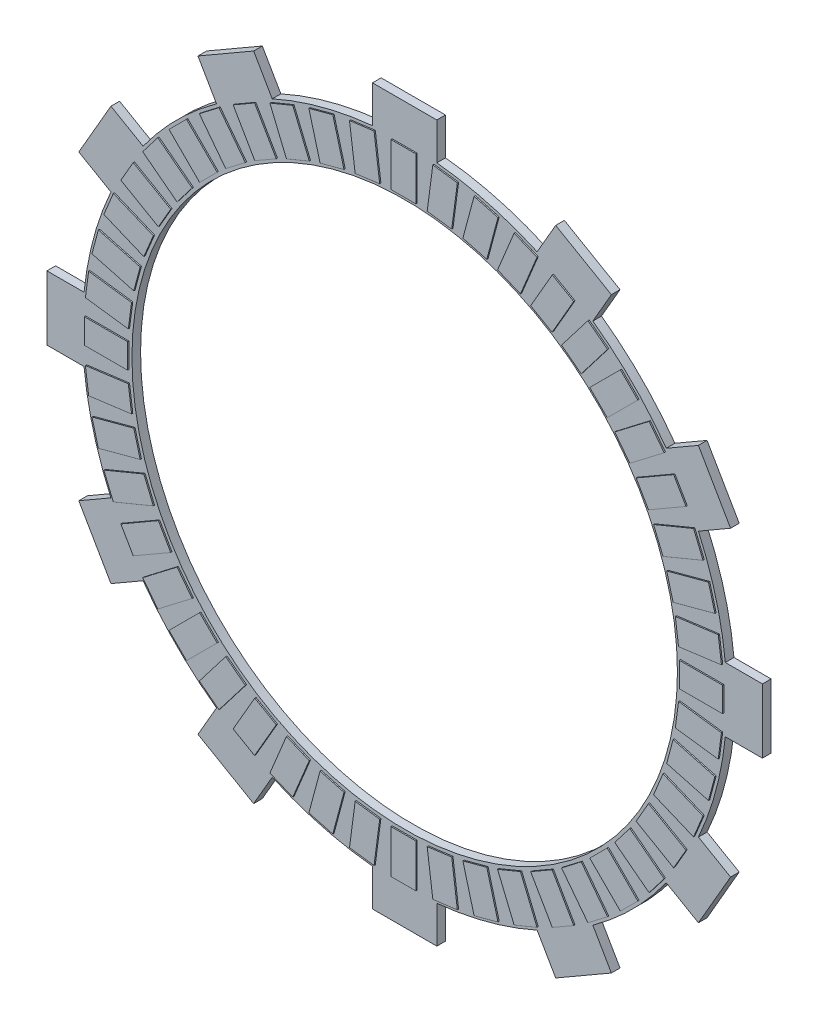
SolidWorks part; units mm, degrees
material "Plain Carbon Steel"
ref_plane "Front Plane" through (0, 0, 0) normal (0, 0, 1) x (1, 0, 0)
ref_plane "Top Plane" through (0, 0, 0) normal (0, 1, 0) x (1, 0, 0)
ref_plane "Right Plane" through (0, 0, 0) normal (1, 0, 0) x (0, 0, -1)
sketch "Sketch1" plane through (0, 0, 0) normal (0, 0, 1) x (1, 0, 0)
  line L0 (0, 0) -> (0, 94.1229) construction
  line L1 (-6.604, 65.8366) -> (-6.604, 73.4566)
  line L2 (-6.604, 73.4566) -> (6.604, 73.4566)
  line L3 (6.604, 73.4566) -> (6.604, 65.8366)
  line L4 (42.4475, 60.3133) -> (38.6375, 53.7142)
  line L5 (27.1991, 60.3182) -> (31.0091, 66.9173)
  line L6 (31.0091, 66.9173) -> (42.4475, 60.3133)
  line L7 (66.9173, 31.0091) -> (60.3182, 27.1991)
  line L8 (53.7142, 38.6375) -> (60.3133, 42.4475)
  line L9 (60.3133, 42.4475) -> (66.9173, 31.0091)
  line L10 (73.4566, -6.604) -> (65.8366, -6.604)
  line L11 (65.8366, 6.604) -> (73.4566, 6.604)
  line L12 (73.4566, 6.604) -> (73.4566, -6.604)
  line L13 (60.3133, -42.4475) -> (53.7142, -38.6375)
  line L14 (60.3182, -27.1991) -> (66.9173, -31.0091)
  line L15 (66.9173, -31.0091) -> (60.3133, -42.4475)
  line L16 (31.0091, -66.9173) -> (27.1991, -60.3182)
  line L17 (38.6375, -53.7142) -> (42.4475, -60.3133)
  line L18 (42.4475, -60.3133) -> (31.0091, -66.9173)
  line L19 (-6.604, -73.4566) -> (-6.604, -65.8366)
  line L20 (6.604, -65.8366) -> (6.604, -73.4566)
  line L21 (6.604, -73.4566) -> (-6.604, -73.4566)
  line L22 (-42.4475, -60.3133) -> (-38.6375, -53.7142)
  line L23 (-27.1991, -60.3182) -> (-31.0091, -66.9173)
  line L24 (-31.0091, -66.9173) -> (-42.4475, -60.3133)
  line L25 (-66.9173, -31.0091) -> (-60.3182, -27.1991)
  line L26 (-53.7142, -38.6375) -> (-60.3133, -42.4475)
  line L27 (-60.3133, -42.4475) -> (-66.9173, -31.0091)
  line L28 (-73.4566, 6.604) -> (-65.8366, 6.604)
  line L29 (-65.8366, -6.604) -> (-73.4566, -6.604)
  line L30 (-73.4566, -6.604) -> (-73.4566, 6.604)
  line L31 (-60.3133, 42.4475) -> (-53.7142, 38.6375)
  line L32 (-60.3182, 27.1991) -> (-66.9173, 31.0091)
  line L33 (-66.9173, 31.0091) -> (-60.3133, 42.4475)
  line L34 (-31.0091, 66.9173) -> (-27.1991, 60.3182)
  line L35 (-38.6375, 53.7142) -> (-42.4475, 60.3133)
  line L36 (-42.4475, 60.3133) -> (-31.0091, 66.9173)
  arc A0 (-6.604, 65.8366) -> (-27.1991, 60.3182) centre (0, 0) ccw
  circle A1 centre (0, 0) radius 56.007
  arc A2 (-38.6375, 53.7142) -> (-53.7142, 38.6375) centre (0, 0) ccw
  arc A3 (-60.3182, 27.1991) -> (-65.8366, 6.604) centre (0, 0) ccw
  arc A4 (-65.8366, -6.604) -> (-60.3182, -27.1991) centre (0, 0) ccw
  arc A5 (-53.7142, -38.6375) -> (-38.6375, -53.7142) centre (0, 0) ccw
  arc A6 (-27.1991, -60.3182) -> (-6.604, -65.8366) centre (0, 0) ccw
  arc A7 (6.604, -65.8366) -> (27.1991, -60.3182) centre (0, 0) ccw
  arc A8 (38.6375, -53.7142) -> (53.7142, -38.6375) centre (0, 0) ccw
  arc A9 (60.3182, -27.1991) -> (65.8366, -6.604) centre (0, 0) ccw
  arc A10 (65.8366, 6.604) -> (60.3182, 27.1991) centre (0, 0) ccw
  arc A11 (53.7142, 38.6375) -> (38.6375, 53.7142) centre (0, 0) ccw
  arc A12 (27.1991, 60.3182) -> (6.604, 65.8366) centre (0, 0) ccw
  point P8 (0, 73.4566)
  point P56 (0, 0)
  dimension "D1" = 10.16
  dimension "D2" = 112.014
  dimension "D3" = 13.208
  dimension "D4" = 7.62
  dimension "D5" = 12
extrude "Boss-Extrude1" add sketch "Sketch1" along normal blind 1.778
sketch "Sketch2" plane through (0, 0, 1.778) normal (0, 0, 1) x (1, 0, 0)
  line L0 (0, 0) -> (0, 131.064) construction
  line L1 (-2.54, 65.532) -> (2.54, 65.532)
  line L2 (2.54, 65.532) -> (2.54, 56.642)
  line L3 (2.54, 56.642) -> (-2.54, 56.642)
  line L4 (-2.54, 56.642) -> (-2.54, 65.532)
  line L5 (4.875, 56.489) -> (6.0354, 65.3029)
  line L6 (6.0354, 65.3029) -> (11.0719, 64.6398)
  line L7 (11.0719, 64.6398) -> (9.9115, 55.8259)
  line L8 (9.9115, 55.8259) -> (4.875, 56.489)
  line L9 (12.2066, 55.3694) -> (14.5075, 63.9565)
  line L10 (14.5075, 63.9565) -> (19.4144, 62.6417)
  line L11 (19.4144, 62.6417) -> (17.1135, 54.0546)
  line L12 (17.1135, 54.0546) -> (12.2066, 55.3694)
  line L13 (19.3293, 53.3024) -> (22.7314, 61.5157)
  line L14 (22.7314, 61.5157) -> (27.4247, 59.5717)
  line L15 (27.4247, 59.5717) -> (24.0226, 51.3584)
  line L16 (24.0226, 51.3584) -> (19.3293, 53.3024)
  line L17 (26.1213, 50.3234) -> (30.5663, 58.0224)
  line L18 (30.5663, 58.0224) -> (34.9657, 55.4824)
  line L19 (34.9657, 55.4824) -> (30.5207, 47.7834)
  line L20 (30.5207, 47.7834) -> (26.1213, 50.3234)
  line L21 (32.4663, 46.4834) -> (37.8782, 53.5363)
  line L22 (37.8782, 53.5363) -> (41.9085, 50.4438)
  line L23 (41.9085, 50.4438) -> (36.4966, 43.3909)
  line L24 (36.4966, 43.3909) -> (32.4663, 46.4834)
  line L25 (38.2559, 41.848) -> (44.5421, 48.1342)
  line L26 (44.5421, 48.1342) -> (48.1342, 44.5421)
  line L27 (48.1342, 44.5421) -> (41.848, 38.2559)
  line L28 (41.848, 38.2559) -> (38.2559, 41.848)
  line L29 (43.3909, 36.4966) -> (50.4438, 41.9085)
  line L30 (50.4438, 41.9085) -> (53.5363, 37.8782)
  line L31 (53.5363, 37.8782) -> (46.4834, 32.4663)
  line L32 (46.4834, 32.4663) -> (43.3909, 36.4966)
  line L33 (47.7834, 30.5207) -> (55.4824, 34.9657)
  line L34 (55.4824, 34.9657) -> (58.0224, 30.5663)
  line L35 (58.0224, 30.5663) -> (50.3234, 26.1213)
  line L36 (50.3234, 26.1213) -> (47.7834, 30.5207)
  line L37 (51.3584, 24.0226) -> (59.5717, 27.4247)
  line L38 (59.5717, 27.4247) -> (61.5157, 22.7314)
  line L39 (61.5157, 22.7314) -> (53.3024, 19.3293)
  line L40 (53.3024, 19.3293) -> (51.3584, 24.0226)
  line L41 (54.0546, 17.1135) -> (62.6417, 19.4144)
  line L42 (62.6417, 19.4144) -> (63.9565, 14.5075)
  line L43 (63.9565, 14.5075) -> (55.3694, 12.2066)
  line L44 (55.3694, 12.2066) -> (54.0546, 17.1135)
  line L45 (55.8259, 9.9115) -> (64.6398, 11.0719)
  line L46 (64.6398, 11.0719) -> (65.3029, 6.0354)
  line L47 (65.3029, 6.0354) -> (56.489, 4.875)
  line L48 (56.489, 4.875) -> (55.8259, 9.9115)
  line L49 (56.642, 2.54) -> (65.532, 2.54)
  line L50 (65.532, 2.54) -> (65.532, -2.54)
  line L51 (65.532, -2.54) -> (56.642, -2.54)
  line L52 (56.642, -2.54) -> (56.642, 2.54)
  line L53 (56.489, -4.875) -> (65.3029, -6.0354)
  line L54 (65.3029, -6.0354) -> (64.6398, -11.0719)
  line L55 (64.6398, -11.0719) -> (55.8259, -9.9115)
  line L56 (55.8259, -9.9115) -> (56.489, -4.875)
  line L57 (55.3694, -12.2066) -> (63.9565, -14.5075)
  line L58 (63.9565, -14.5075) -> (62.6417, -19.4144)
  line L59 (62.6417, -19.4144) -> (54.0546, -17.1135)
  line L60 (54.0546, -17.1135) -> (55.3694, -12.2066)
  line L61 (53.3024, -19.3293) -> (61.5157, -22.7314)
  line L62 (61.5157, -22.7314) -> (59.5717, -27.4247)
  line L63 (59.5717, -27.4247) -> (51.3584, -24.0226)
  line L64 (51.3584, -24.0226) -> (53.3024, -19.3293)
  line L65 (50.3234, -26.1213) -> (58.0224, -30.5663)
  line L66 (58.0224, -30.5663) -> (55.4824, -34.9657)
  line L67 (55.4824, -34.9657) -> (47.7834, -30.5207)
  line L68 (47.7834, -30.5207) -> (50.3234, -26.1213)
  line L69 (46.4834, -32.4663) -> (53.5363, -37.8782)
  line L70 (53.5363, -37.8782) -> (50.4438, -41.9085)
  line L71 (50.4438, -41.9085) -> (43.3909, -36.4966)
  line L72 (43.3909, -36.4966) -> (46.4834, -32.4663)
  line L73 (41.848, -38.2559) -> (48.1342, -44.5421)
  line L74 (48.1342, -44.5421) -> (44.5421, -48.1342)
  line L75 (44.5421, -48.1342) -> (38.2559, -41.848)
  line L76 (38.2559, -41.848) -> (41.848, -38.2559)
  line L77 (36.4966, -43.3909) -> (41.9085, -50.4438)
  line L78 (41.9085, -50.4438) -> (37.8782, -53.5363)
  line L79 (37.8782, -53.5363) -> (32.4663, -46.4834)
  line L80 (32.4663, -46.4834) -> (36.4966, -43.3909)
  line L81 (30.5207, -47.7834) -> (34.9657, -55.4824)
  line L82 (34.9657, -55.4824) -> (30.5663, -58.0224)
  line L83 (30.5663, -58.0224) -> (26.1213, -50.3234)
  line L84 (26.1213, -50.3234) -> (30.5207, -47.7834)
  line L85 (24.0226, -51.3584) -> (27.4247, -59.5717)
  line L86 (27.4247, -59.5717) -> (22.7314, -61.5157)
  line L87 (22.7314, -61.5157) -> (19.3293, -53.3024)
  line L88 (19.3293, -53.3024) -> (24.0226, -51.3584)
  line L89 (17.1135, -54.0546) -> (19.4144, -62.6417)
  line L90 (19.4144, -62.6417) -> (14.5075, -63.9565)
  line L91 (14.5075, -63.9565) -> (12.2066, -55.3694)
  line L92 (12.2066, -55.3694) -> (17.1135, -54.0546)
  line L93 (9.9115, -55.8259) -> (11.0719, -64.6398)
  line L94 (11.0719, -64.6398) -> (6.0354, -65.3029)
  line L95 (6.0354, -65.3029) -> (4.875, -56.489)
  line L96 (4.875, -56.489) -> (9.9115, -55.8259)
  line L97 (2.54, -56.642) -> (2.54, -65.532)
  line L98 (2.54, -65.532) -> (-2.54, -65.532)
  line L99 (-2.54, -65.532) -> (-2.54, -56.642)
  line L100 (-2.54, -56.642) -> (2.54, -56.642)
  line L101 (-4.875, -56.489) -> (-6.0354, -65.3029)
  line L102 (-6.0354, -65.3029) -> (-11.0719, -64.6398)
  line L103 (-11.0719, -64.6398) -> (-9.9115, -55.8259)
  line L104 (-9.9115, -55.8259) -> (-4.875, -56.489)
  line L105 (-12.2066, -55.3694) -> (-14.5075, -63.9565)
  line L106 (-14.5075, -63.9565) -> (-19.4144, -62.6417)
  line L107 (-19.4144, -62.6417) -> (-17.1135, -54.0546)
  line L108 (-17.1135, -54.0546) -> (-12.2066, -55.3694)
  line L109 (-19.3293, -53.3024) -> (-22.7314, -61.5157)
  line L110 (-22.7314, -61.5157) -> (-27.4247, -59.5717)
  line L111 (-27.4247, -59.5717) -> (-24.0226, -51.3584)
  line L112 (-24.0226, -51.3584) -> (-19.3293, -53.3024)
  line L113 (-26.1213, -50.3234) -> (-30.5663, -58.0224)
  line L114 (-30.5663, -58.0224) -> (-34.9657, -55.4824)
  line L115 (-34.9657, -55.4824) -> (-30.5207, -47.7834)
  line L116 (-30.5207, -47.7834) -> (-26.1213, -50.3234)
  line L117 (-32.4663, -46.4834) -> (-37.8782, -53.5363)
  line L118 (-37.8782, -53.5363) -> (-41.9085, -50.4438)
  line L119 (-41.9085, -50.4438) -> (-36.4966, -43.3909)
  line L120 (-36.4966, -43.3909) -> (-32.4663, -46.4834)
  line L121 (-38.2559, -41.848) -> (-44.5421, -48.1342)
  line L122 (-44.5421, -48.1342) -> (-48.1342, -44.5421)
  line L123 (-48.1342, -44.5421) -> (-41.848, -38.2559)
  line L124 (-41.848, -38.2559) -> (-38.2559, -41.848)
  line L125 (-43.3909, -36.4966) -> (-50.4438, -41.9085)
  line L126 (-50.4438, -41.9085) -> (-53.5363, -37.8782)
  line L127 (-53.5363, -37.8782) -> (-46.4834, -32.4663)
  line L128 (-46.4834, -32.4663) -> (-43.3909, -36.4966)
  line L129 (-47.7834, -30.5207) -> (-55.4824, -34.9657)
  line L130 (-55.4824, -34.9657) -> (-58.0224, -30.5663)
  line L131 (-58.0224, -30.5663) -> (-50.3234, -26.1213)
  line L132 (-50.3234, -26.1213) -> (-47.7834, -30.5207)
  line L133 (-51.3584, -24.0226) -> (-59.5717, -27.4247)
  line L134 (-59.5717, -27.4247) -> (-61.5157, -22.7314)
  line L135 (-61.5157, -22.7314) -> (-53.3024, -19.3293)
  line L136 (-53.3024, -19.3293) -> (-51.3584, -24.0226)
  line L137 (-54.0546, -17.1135) -> (-62.6417, -19.4144)
  line L138 (-62.6417, -19.4144) -> (-63.9565, -14.5075)
  line L139 (-63.9565, -14.5075) -> (-55.3694, -12.2066)
  line L140 (-55.3694, -12.2066) -> (-54.0546, -17.1135)
  line L141 (-55.8259, -9.9115) -> (-64.6398, -11.0719)
  line L142 (-64.6398, -11.0719) -> (-65.3029, -6.0354)
  line L143 (-65.3029, -6.0354) -> (-56.489, -4.875)
  line L144 (-56.489, -4.875) -> (-55.8259, -9.9115)
  line L145 (-56.642, -2.54) -> (-65.532, -2.54)
  line L146 (-65.532, -2.54) -> (-65.532, 2.54)
  line L147 (-65.532, 2.54) -> (-56.642, 2.54)
  line L148 (-56.642, 2.54) -> (-56.642, -2.54)
  line L149 (-56.489, 4.875) -> (-65.3029, 6.0354)
  line L150 (-65.3029, 6.0354) -> (-64.6398, 11.0719)
  line L151 (-64.6398, 11.0719) -> (-55.8259, 9.9115)
  line L152 (-55.8259, 9.9115) -> (-56.489, 4.875)
  line L153 (-55.3694, 12.2066) -> (-63.9565, 14.5075)
  line L154 (-63.9565, 14.5075) -> (-62.6417, 19.4144)
  line L155 (-62.6417, 19.4144) -> (-54.0546, 17.1135)
  line L156 (-54.0546, 17.1135) -> (-55.3694, 12.2066)
  line L157 (-53.3024, 19.3293) -> (-61.5157, 22.7314)
  line L158 (-61.5157, 22.7314) -> (-59.5717, 27.4247)
  line L159 (-59.5717, 27.4247) -> (-51.3584, 24.0226)
  line L160 (-51.3584, 24.0226) -> (-53.3024, 19.3293)
  line L161 (-50.3234, 26.1213) -> (-58.0224, 30.5663)
  line L162 (-58.0224, 30.5663) -> (-55.4824, 34.9657)
  line L163 (-55.4824, 34.9657) -> (-47.7834, 30.5207)
  line L164 (-47.7834, 30.5207) -> (-50.3234, 26.1213)
  line L165 (-46.4834, 32.4663) -> (-53.5363, 37.8782)
  line L166 (-53.5363, 37.8782) -> (-50.4438, 41.9085)
  line L167 (-50.4438, 41.9085) -> (-43.3909, 36.4966)
  line L168 (-43.3909, 36.4966) -> (-46.4834, 32.4663)
  line L169 (-41.848, 38.2559) -> (-48.1342, 44.5421)
  line L170 (-48.1342, 44.5421) -> (-44.5421, 48.1342)
  line L171 (-44.5421, 48.1342) -> (-38.2559, 41.848)
  line L172 (-38.2559, 41.848) -> (-41.848, 38.2559)
  line L173 (-36.4966, 43.3909) -> (-41.9085, 50.4438)
  line L174 (-41.9085, 50.4438) -> (-37.8782, 53.5363)
  line L175 (-37.8782, 53.5363) -> (-32.4663, 46.4834)
  line L176 (-32.4663, 46.4834) -> (-36.4966, 43.3909)
  line L177 (-30.5207, 47.7834) -> (-34.9657, 55.4824)
  line L178 (-34.9657, 55.4824) -> (-30.5663, 58.0224)
  line L179 (-30.5663, 58.0224) -> (-26.1213, 50.3234)
  line L180 (-26.1213, 50.3234) -> (-30.5207, 47.7834)
  line L181 (-24.0226, 51.3584) -> (-27.4247, 59.5717)
  line L182 (-27.4247, 59.5717) -> (-22.7314, 61.5157)
  line L183 (-22.7314, 61.5157) -> (-19.3293, 53.3024)
  line L184 (-19.3293, 53.3024) -> (-24.0226, 51.3584)
  line L185 (-17.1135, 54.0546) -> (-19.4144, 62.6417)
  line L186 (-19.4144, 62.6417) -> (-14.5075, 63.9565)
  line L187 (-14.5075, 63.9565) -> (-12.2066, 55.3694)
  line L188 (-12.2066, 55.3694) -> (-17.1135, 54.0546)
  line L189 (-9.9115, 55.8259) -> (-11.0719, 64.6398)
  line L190 (-11.0719, 64.6398) -> (-6.0354, 65.3029)
  line L191 (-6.0354, 65.3029) -> (-4.875, 56.489)
  line L192 (-4.875, 56.489) -> (-9.9115, 55.8259)
  point P7 (0, 65.532)
  point P199 (0, 0)
  dimension "D1" = 8.89
  dimension "D2" = 5.08
  dimension "D3" = 56.642
  dimension "D4" = 48
extrude "Boss-Extrude2" add sketch "Sketch2" along normal blind 0.254 and the other way blind 2.032
